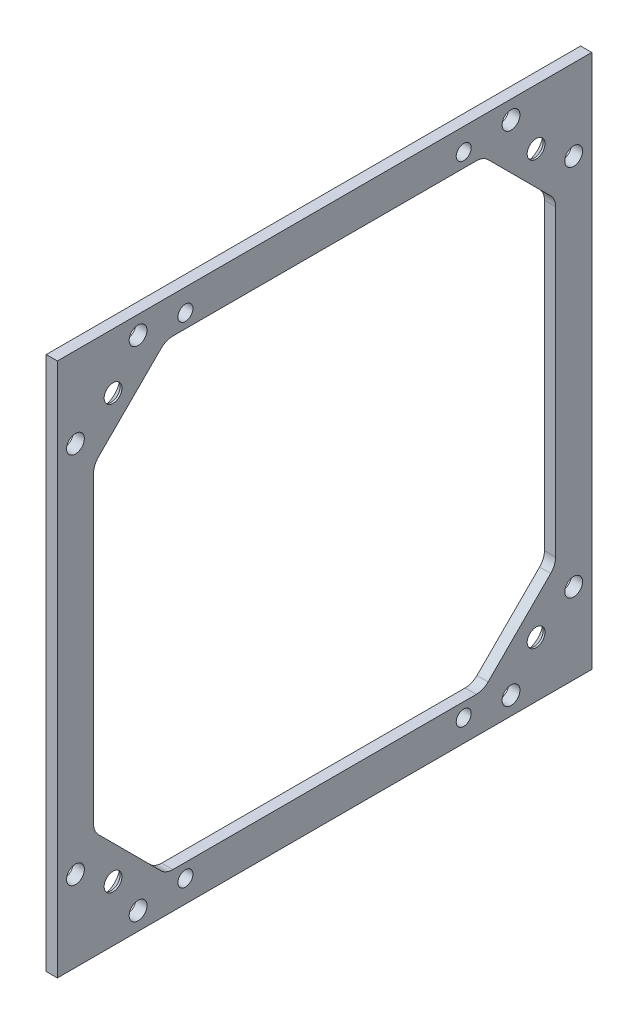
SolidWorks part; units mm, degrees
ref_plane "Front Plane" through (0, 0, 0) normal (0, 0, 1) x (1, 0, 0)
ref_plane "Top Plane" through (0, 0, 0) normal (0, 1, 0) x (1, 0, 0)
ref_plane "Right Plane" through (0, 0, 0) normal (1, 0, 0) x (0, 0, -1)
sketch "Sketch2" plane through (-51.4936, 0, 0) normal (-1, 0, 0) x (0, 0, 1)
  line L0 (0.9347, 3.4519) -> (7.4347, 3.4519)
  line L1 (7.4347, 3.4519) -> (7.4347, 86.4519)
  line L2 (0.9347, 92.9519) -> (-82.0653, 92.9519)
  line L3 (-88.5653, 86.4519) -> (-88.5653, 3.4519)
  line L4 (-82.0653, -3.0481) -> (0.9347, -3.0481)
  line L5 (0.9347, -3.0481) -> (0.9347, 3.4519)
  line L6 (-82.0653, -3.0481) -> (-82.0653, 3.4519)
  line L7 (-82.0653, 3.4519) -> (-88.5653, 3.4519)
  line L9 (-82.0653, 73.4519) -> (-82.0653, 16.4519)
  line L11 (-88.5653, 86.4519) -> (-82.0653, 86.4519)
  line L12 (-82.0653, 92.9519) -> (-82.0653, 86.4519)
  line L13 (-69.0653, 3.4519) -> (-12.0653, 3.4519)
  line L14 (-82.0653, 73.4519) -> (-69.0653, 86.4519)
  line L15 (7.4347, 86.4519) -> (0.9347, 86.4519)
  line L16 (0.9347, 92.9519) -> (0.9347, 86.4519)
  line L17 (0.9347, 16.4519) -> (0.9347, 73.4519)
  line L18 (-12.0653, 86.4519) -> (0.9347, 73.4519)
  line L19 (-12.0653, 86.4519) -> (-69.0653, 86.4519)
  line L28 (-12.0653, 3.4519) -> (0.9347, 16.4519)
  line L29 (-82.0653, 16.4519) -> (-69.0653, 3.4519)
  dimension "D21" = 13
  dimension "D1" = 6.5
  dimension "D2" = 6.5
  dimension "D3" = 6.5
  dimension "D4" = 6.5
  dimension "D5" = 6.5
  dimension "D6" = 6.5
  dimension "D7" = 13
  dimension "D8" = 6.5
  dimension "D9" = 6.5
  dimension "D10" = 13
  dimension "D11" = 6.5
  dimension "D12" = 6.5
  dimension "D14" = 13
  dimension "D15" = 13
  dimension "D16" = 13
  dimension "D17" = 13
  dimension "D18" = 13
  dimension "D19" = 83
  dimension "D20" = 83
extrude "Boss-Extrude2" add sketch "Sketch2" along normal blind 2
hole_wizard "Ø3.2 (3.2) Diameter Hole3" positions "Sketch19" profile "Sketch18" hole size "Ø3.2" standard "Ansi Metric" end condition up to next
sketch "Sketch19" plane through (-53.4936, 0, 0) normal (-1, 0, 0) x (0, 0, 1)
  line L0 (-82.0653, 3.4519) -> (-82.0653, -3.0481) construction
  line L1 (-82.0653, -3.0481) -> (0.9347, -3.0481) construction
  line L2 (-88.5653, 86.4519) -> (-88.5653, 3.4519) construction
  line L4 (-88.5653, 3.4519) -> (-82.0653, 3.4519) construction
  line L5 (0.9347, -3.0481) -> (0.9347, 3.4519) construction
  line L6 (0.9347, 3.4519) -> (7.4347, 3.4519) construction
  line L7 (7.4347, 3.4519) -> (7.4347, 86.4519) construction
  line L8 (7.4347, 86.4519) -> (0.9347, 86.4519) construction
  line L9 (0.9347, 86.4519) -> (0.9347, 92.9519) construction
  line L10 (0.9347, 92.9519) -> (-82.0653, 92.9519) construction
  line L11 (-82.0653, 92.9519) -> (-82.0653, 86.4519) construction
  line L12 (-82.0653, 86.4519) -> (-88.5653, 86.4519) construction
  point P0 (-74.0653, 0.2019)
  point P6 (-85.3153, 11.4519)
  point P8 (-85.3153, 78.4519)
  point P10 (-74.0653, 89.7019)
  point P12 (-7.0653, 89.7019)
  point P14 (4.1847, 78.4519)
  point P16 (4.1847, 11.4519)
  point P18 (-7.0653, 0.2019)
  point P56 (-82.0653, 89.7019)
  point P59 (-85.3153, 86.4519)
  dimension "D1" = 8
  dimension "D2" = 3.25
  dimension "D3" = 3.25
  dimension "D4" = 8
  dimension "D5" = 8
  dimension "D6" = 8
  dimension "D7" = 3.25
  dimension "D8" = 8
  dimension "D9" = 8
  dimension "D10" = 3.25
  dimension "D11" = 8
  dimension "D12" = 8
sketch "Sketch18" plane through (-53.4936, 0.2019, -74.0653) normal (0, 1, 0) x (0, 0, 1)
  line L0 (0, 0) -> (0, 2)
  line L1 (0, 2) -> (1.6, 2)
  line L2 (1.6, 2) -> (1.6, 0)
  line L5 (1.6, 0) -> (0, 0)
  line L11 (0, -6.35) -> (0, 107.95) construction
  dimension "Thru Hole Dia." = 3.2
  dimension "Thru Hole Depth" = 2
hole_wizard "CSK for M3 Flat Countersunk Head Screw5" positions "3DSketch2" profile "Sketch24" countersink size "M3" standard "JIS" end condition up to next
sketch3d "3DSketch2"
  line L0 (-53.4936, 3.4519, -82.0653) -> (-53.4936, -3.0481, -82.0653) construction
  line L1 (-53.4936, 3.4519, -88.5653) -> (-53.4936, 3.4519, -82.0653) construction
  line L2 (-53.4936, 92.9519, -82.0653) -> (-53.4936, 86.4519, -82.0653) construction
  line L3 (-53.4936, 86.4519, -82.0653) -> (-53.4936, 86.4519, -88.5653) construction
  line L4 (-53.4936, 86.4519, 0.9347) -> (-53.4936, 92.9519, 0.9347) construction
  line L5 (-53.4936, 86.4519, 7.4347) -> (-53.4936, 86.4519, 0.9347) construction
  line L6 (-53.4936, -3.0481, 0.9347) -> (-53.4936, 3.4519, 0.9347) construction
  line L7 (-53.4936, 3.4519, 0.9347) -> (-53.4936, 3.4519, 7.4347) construction
  point P0 (-53.4936, 6.9519, -78.5653)
  point P2 (-53.4936, 82.9519, -78.5653)
  point P4 (-53.4936, 82.9519, -2.5653)
  point P19 (-53.4936, 6.9519, -2.5653)
  dimension "D1" = 3.5
  dimension "D2" = 3.5
  dimension "D3" = 3.5
  dimension "D4" = 3.5
  dimension "D5" = 3.5
  dimension "D6" = 3.5
  dimension "D7" = 3.5
  dimension "D8" = 3.5
sketch "Sketch24" plane through (-53.4936, 6.9519, -78.5653) normal (0, 1, 0) x (0, 0, 1)
  line L0 (0, 0) -> (0, 2)
  line L1 (0, 2) -> (1.6, 2)
  line L2 (1.6, 2) -> (1.6, 1.65)
  line L3 (1.6, 1.65) -> (3.25, 0)
  line L5 (3.25, 0) -> (0, 0)
  line L6 (-1.6, 1.65) -> (-3.25, 0) construction
  line L11 (0, -6.35) -> (0, 107.95) construction
  dimension "Thru Hole Dia." = 3.2
  dimension "Thru Hole Depth" = 2
  dimension "Near C'Sink Dia." = 6.5
  dimension "Near C'Sink Angle" = 90
hole_wizard "Ø2.7 (2.7) Diameter Hole1" positions "3DSketch3" profile "Sketch25" hole size "Ø2.7" standard "Ansi Metric" end condition up to next
sketch3d "3DSketch3"
  line L0 (-53.4936, 92.9519, 0.9347) -> (-53.4936, 92.9519, -82.0653) construction
  line L3 (-53.4936, 3.4519, 7.4347) -> (-53.4936, 86.4519, 7.4347) construction
  line L4 (-53.4936, -3.0481, -82.0653) -> (-53.4936, -3.0481, 0.9347) construction
  line L6 (-53.4936, 86.4519, -88.5653) -> (-53.4936, 3.4519, -88.5653) construction
  point P0 (-53.4936, 88.9519, -65.5653)
  point P2 (-53.4936, 88.9519, -15.5653)
  point P4 (-53.4936, 0.9519, -65.5653)
  point P6 (-53.4936, 0.9519, -15.5653)
  dimension "D1" = 4
  dimension "D2" = 23
  dimension "D3" = 4
  dimension "D4" = 23
  dimension "D5" = 4
  dimension "D6" = 23
  dimension "D7" = 23
  dimension "D8" = 4
sketch "Sketch25" plane through (-53.4936, 88.9519, -65.5653) normal (0, 1, 0) x (0, 0, 1)
  line L0 (0, 0) -> (0, 2)
  line L1 (0, 2) -> (1.35, 2)
  line L2 (1.35, 2) -> (1.35, 0)
  line L5 (1.35, 0) -> (0, 0)
  line L11 (0, -6.35) -> (0, 107.95) construction
  dimension "Thru Hole Dia." = 2.7
  dimension "Thru Hole Depth" = 2
fillet "Fillet1" radius 3 8 edges at (-52.4936, 16.4519, 0.9347) (-52.4936, 3.4519, -12.0653) (-52.4936, 3.4519, -69.0653) (-52.4936, 16.4519, -82.0653) (-52.4936, 73.4519, 0.9347) (-52.4936, 86.4519, -12.0653) (-52.4936, 73.4519, -82.0653) (-52.4936, 86.4519, -69.0653)
sketch "Sketch26" plane through (-51.4936, 0, 0) normal (1, 0, 0) x (0, 0, -1)
  line L1 (-0.9347, 86.4519) -> (-7.4347, 86.4519)
  line L2 (-0.9347, 86.4519) -> (-0.9347, 92.9519)
  line L3 (-0.9347, 92.9519) -> (-7.4347, 92.9519)
  line L4 (-7.4347, 86.4519) -> (-7.4347, 92.9519)
  line L5 (82.0653, 86.4519) -> (88.5653, 86.4519)
  line L6 (82.0653, 86.4519) -> (82.0653, 92.9519)
  line L7 (82.0653, 92.9519) -> (88.5653, 92.9519)
  line L8 (88.5653, 86.4519) -> (88.5653, 92.9519)
  line L9 (82.0653, 3.4519) -> (88.5653, 3.4519)
  line L10 (82.0653, 3.4519) -> (82.0653, -3.0481)
  line L11 (82.0653, -3.0481) -> (88.5653, -3.0481)
  line L12 (88.5653, 3.4519) -> (88.5653, -3.0481)
  line L13 (-0.9347, 3.4519) -> (-7.4347, 3.4519)
  line L14 (-0.9347, 3.4519) -> (-0.9347, -3.0481)
  line L15 (-0.9347, -3.0481) -> (-7.4347, -3.0481)
  line L16 (-7.4347, 3.4519) -> (-7.4347, -3.0481)
  dimension "D1" = 6.5
extrude "Boss-Extrude3" add sketch "Sketch26" against normal blind 2
